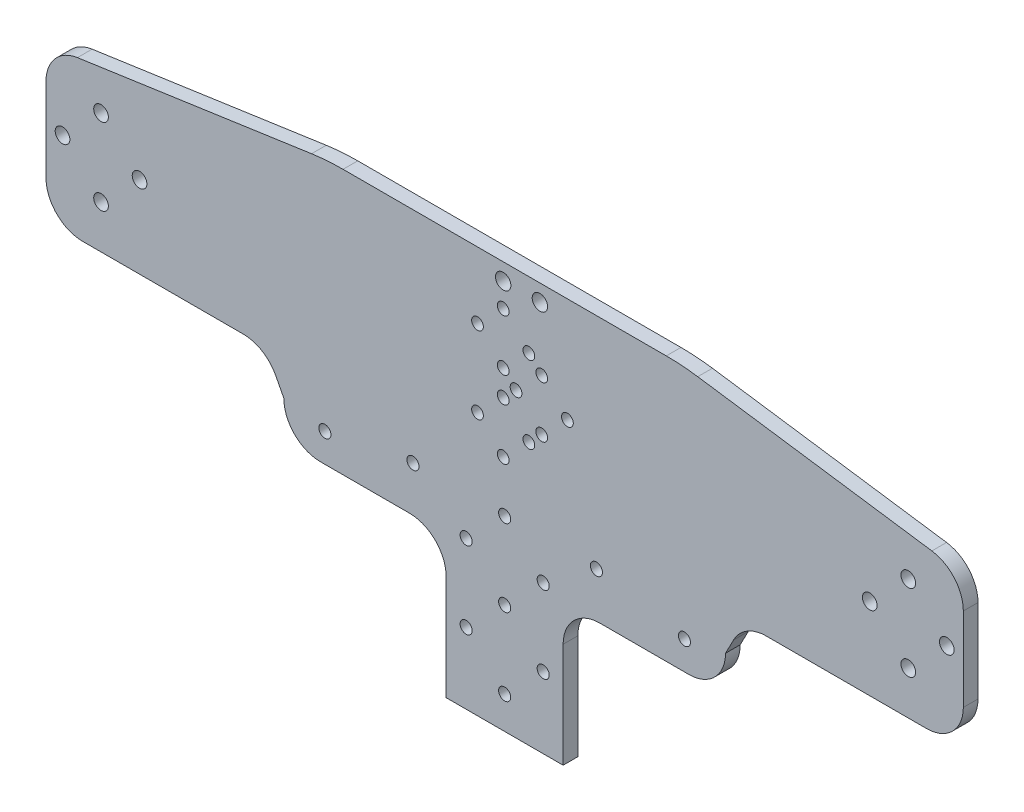
SolidWorks part; units mm, degrees
ref_plane "前视基准面" through (0, 0, 0) normal (0, 0, 1) x (1, 0, 0)
ref_plane "上视基准面" through (0, 0, 0) normal (0, 1, 0) x (1, 0, 0)
ref_plane "右视基准面" through (0, 0, 0) normal (1, 0, 0) x (0, 0, -1)
other "Configuration Table"
sketch "草图1" plane through (0, 0, 0) normal (0, 0, 1) x (1, 0, 0)
  line L16 (-71.2575, -5.3843) -> (-115, -5.3843)
  line L19 (-125, 4.6157) -> (-125, 27.3731)
  line L25 (15.9335, -35.0094) -> (15.9335, -63.561)
  line L26 (50.1835, -25.0094) -> (25.9335, -25.0094)
  line L29 (125, 4.6157) -> (125, 27.3731)
  line L35 (71.2575, -5.3843) -> (115, -5.3843)
  line L38 (-62.3834, -10.7745) -> (-60.1835, -15.0094)
  line L41 (60.1835, -15.0094) -> (62.3834, -10.7745)
  line L44 (0.1599, 47.1052) -> (-44.0428, 47.1052)
  line L45 (-52.6219, 46.4887) -> (-116.4299, 37.2704)
  line L46 (-111.6556, 16.9345) -> (148.2953, 11.8822) construction
  line L47 (125, 4.6157) -> (125, 36.0322)
  line L48 (52.6219, 46.4887) -> (116.4299, 37.2704)
  line L49 (-0.1599, 47.1052) -> (44.0428, 47.1052)
  line L84 (-50.1835, -25.0094) -> (-25.9335, -25.0094)
  line L85 (-15.9335, -35.0094) -> (-15.9335, -63.561)
  line L86 (-15.9335, -63.561) -> (15.9335, -63.561)
  line L87 (0, -63.561) -> (0, 95.9708) construction
  circle A114 centre (-110, 16.9024) radius 10.5 construction
  circle A115 centre (-110, 27.4024) radius 2
  circle A116 centre (-99.5, 16.9024) radius 2
  circle A117 centre (-110, 6.4024) radius 2
  circle A118 centre (-120.5, 16.9024) radius 2
  arc A133 (-25.9335, -25.0094) -> (-15.9335, -35.0094) centre (-25.9335, -35.0094) cw
  arc A136 (-50.1835, -25.0094) -> (-60.1835, -15.0094) centre (-50.1835, -15.0094) cw
  circle A141 centre (110, 16.9024) radius 10.5 construction
  arc A143 (50.1835, -25.0094) -> (60.1835, -15.0094) centre (50.1835, -15.0094) ccw
  arc A144 (25.9335, -25.0094) -> (15.9335, -35.0094) centre (25.9335, -35.0094) ccw
  circle A145 centre (120.5, 16.9024) radius 2
  circle A146 centre (110, 6.4024) radius 2
  circle A147 centre (99.5, 16.9024) radius 2
  circle A148 centre (110, 27.4024) radius 2
  circle A150 centre (0, -54.7094) radius 1.65
  circle A151 centre (-10.5, -44.2094) radius 1.65
  circle A152 centre (10.5, -44.2094) radius 1.65
  circle A153 centre (0, -33.7094) radius 1.65
  circle A154 centre (0, -12.7094) radius 1.65
  circle A155 centre (-10.5, -23.2094) radius 1.65
  circle A158 centre (-25, -12.7094) radius 1.65
  circle A159 centre (-49, -17.2094) radius 1.65
  circle A160 centre (10.5, -23.2094) radius 1.65
  circle A162 centre (25, -12.7094) radius 1.65
  circle A163 centre (49, -17.2094) radius 1.65
  arc A168 (125, 4.6157) -> (115, -5.3843) centre (115, 4.6157) cw
  arc A169 (-115, -5.3843) -> (-125, 4.6157) centre (-115, 4.6157) cw
  circle A170 centre (9.6, 42.5322) radius 2.1
  circle A171 centre (-0.4, 42.5322) radius 2.1
  circle A172 centre (-0.4, 1.0322) radius 1.6
  circle A173 centre (-7.4, 8.0322) radius 1.6
  circle A174 centre (6.6, 8.0322) radius 1.6
  circle A175 centre (10.1, 11.5322) radius 1.6
  circle A176 centre (-0.4, 15.0322) radius 1.6
  circle A177 centre (6.6, 29.0322) radius 1.6
  circle A178 centre (17.1, 18.5322) radius 1.6
  circle A179 centre (10.1, 25.5322) radius 1.6
  circle A180 centre (3.1, 18.5322) radius 1.6
  circle A181 centre (-0.4, 22.0322) radius 1.6
  circle A182 centre (-7.4, 29.0322) radius 1.6
  circle A183 centre (-0.4, 36.0322) radius 1.6
  arc A184 (62.3834, -10.7745) -> (71.2575, -5.3843) centre (71.2575, -15.3843) cw
  arc A185 (-71.2575, -5.3843) -> (-62.3834, -10.7745) centre (-71.2575, -15.3843) cw
  arc A186 (115, -5.3843) -> (125, 4.6157) centre (115, 4.6157) ccw
  arc A187 (125, 27.3731) -> (116.4299, 37.2704) centre (115, 27.3731) ccw
  arc A188 (-116.4299, 37.2704) -> (-125, 27.3731) centre (-115, 27.3731) ccw
  arc A189 (52.6219, 46.4887) -> (44.0428, 47.1052) centre (44.0428, -12.8948) ccw
  arc A190 (-44.0428, 47.1052) -> (-52.6219, 46.4887) centre (-44.0428, -12.8948) ccw
  point P11 (-110, 12.9121)
  point P13 (65.1835, -5.3843)
  point P43 (60.1835, -10.3086)
  point P44 (60.1835, -5.3843)
  point P45 (101.0375, 25.299)
  point P48 (-15.9335, -25.0094)
  point P50 (101.0375, -5.3843)
  point P51 (60.1835, -25.0094)
  point P52 (15.9335, -25.0094)
  point P60 (-60.1835, -25.0094)
  point P64 (-101.0375, -5.3843)
  point P67 (-101.0375, 25.299)
  point P73 (-60.1835, -5.3843)
  point P84 (-40.6417, 52.6589)
  point P85 (-30.3679, 48.6939)
  point P86 (0, 0)
  point P87 (-45.8619, 47.4653)
  point P89 (0, 0)
  point P90 (0, 0)
  point P94 (125, -5.3843)
  point P97 (-125, -5.3843)
  point P126 (-65.1835, -5.3843)
  point P130 (-125, 36.0322)
  point P133 (48.3545, 47.1052)
  point P136 (-48.3545, 47.1052)
  point P137 (0.1599, 47.1052)
  point P284 (-60.1835, -10.3086)
  point P285 (0, -0.3086)
  point P324 (0, 43.7163)
  dimension "D3" = 4
  dimension "D7" = 3.3
  dimension "D11" = 3.2
  dimension "D1" = 220
  dimension "D2" = 21
  dimension "D4" = 31.867
  dimension "D5" = 10
  dimension "D6" = 250
  dimension "D8" = 10
  dimension "D9" = 4.2
  dimension "D10" = 4.2
  dimension "D12" = 60
extrude "凸台-拉伸1" add sketch "草图1" along normal blind 4 contours L44 A190 L45 A188 L19 A169 L16 A185 L38 A136 L84 A133 L85 L86 L25 A144 L26 A143 L41 A184 L35 A168 L29 A187 L48 A189 L49 A148 A146 A115 A116 A117 A118 A145 A147 A150 A151 A152
